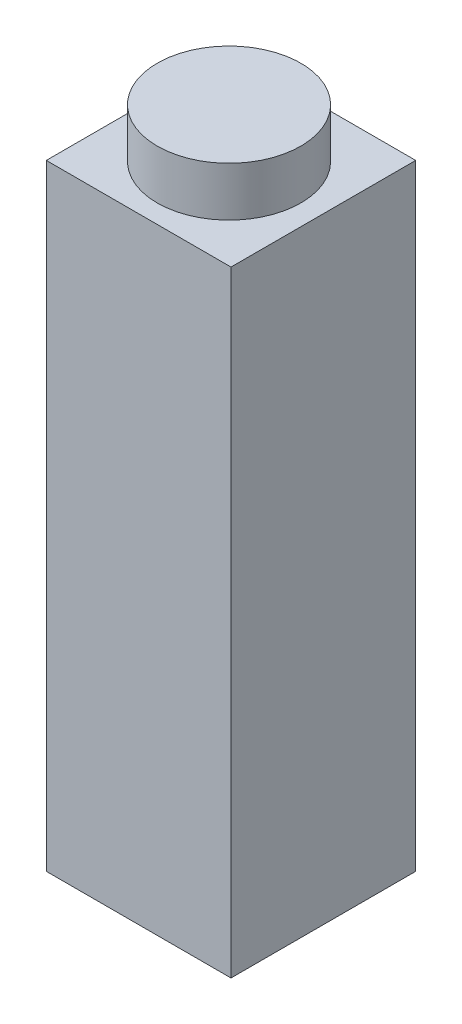
SolidWorks part; units mm, degrees
ref_plane "Front Plane" through (0, 0, 0) normal (0, 0, 1) x (1, 0, 0)
ref_plane "Top Plane" through (0, 0, 0) normal (0, 1, 0) x (1, 0, 0)
ref_plane "Right Plane" through (0, 0, 0) normal (1, 0, 0) x (0, 0, -1)
sketch "Sketch1" plane through (0, 0, 0) normal (0, 1, 0) x (1, 0, 0)
  line L1 (-2.25, -2.25) -> (2.25, -2.25)
  line L2 (-2.25, -2.25) -> (-2.25, 2.25)
  line L3 (-2.25, 2.25) -> (2.25, 2.25)
  line L4 (2.25, -2.25) -> (2.25, 2.25)
  line L5 (-2.25, -2.25) -> (2.25, 2.25) construction
  line L6 (-2.25, 2.25) -> (2.25, -2.25) construction
  point P0 (0, 0)
  dimension "D1" = 4.5
  dimension "D2" = 4.5
extrude "Boss-Extrude1" add sketch "Sketch1" along normal blind 15
sketch "Sketch2" plane through (0, 0, 0) normal (0, -1, 0) x (1, 0, 0)
  circle A0 centre (0, 0) radius 1
  dimension "D1" = 2
extrude "Cut-Extrude1" cut sketch "Sketch2" against normal blind 0.5
sketch "Sketch4" plane through (0, 15, 0) normal (0, 1, 0) x (1, 0, 0)
  circle A0 centre (0, -0.0477) radius 1.75
  dimension "D1" = 3.5
extrude "Boss-Extrude2" add sketch "Sketch4" along normal blind 1.2
